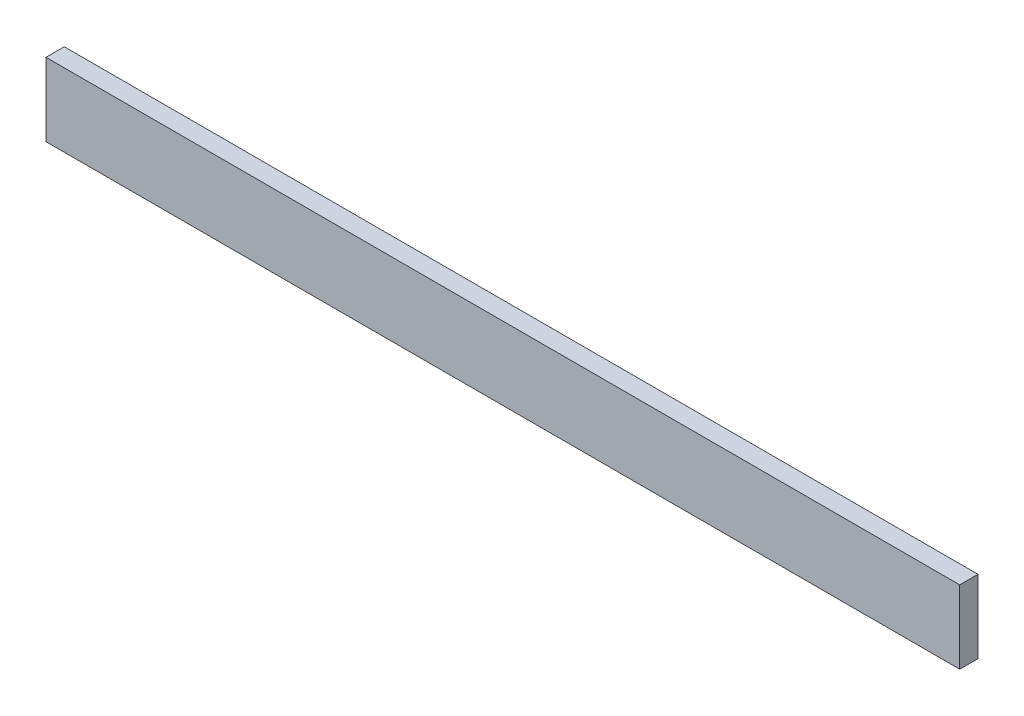
SolidWorks part; units mm, degrees
ref_plane "Front Plane" through (0, 0, 0) normal (0, 0, 1) x (1, 0, 0)
ref_plane "Top Plane" through (0, 0, 0) normal (0, 1, 0) x (1, 0, 0)
ref_plane "Right Plane" through (0, 0, 0) normal (1, 0, 0) x (0, 0, -1)
sketch "Sketch1" plane through (0, 0, 0) normal (0, 0, 1) x (1, 0, 0)
  line L0 (0, 0) -> (250, 0)
  line L1 (250, 0) -> (250, 20)
  line L2 (250, 20) -> (0, 20)
  line L3 (0, 20) -> (0, 0)
  dimension "D1" = 250
  dimension "D2" = 20
extrude "Boss-Extrude1" add sketch "Sketch1" along normal blind 5
